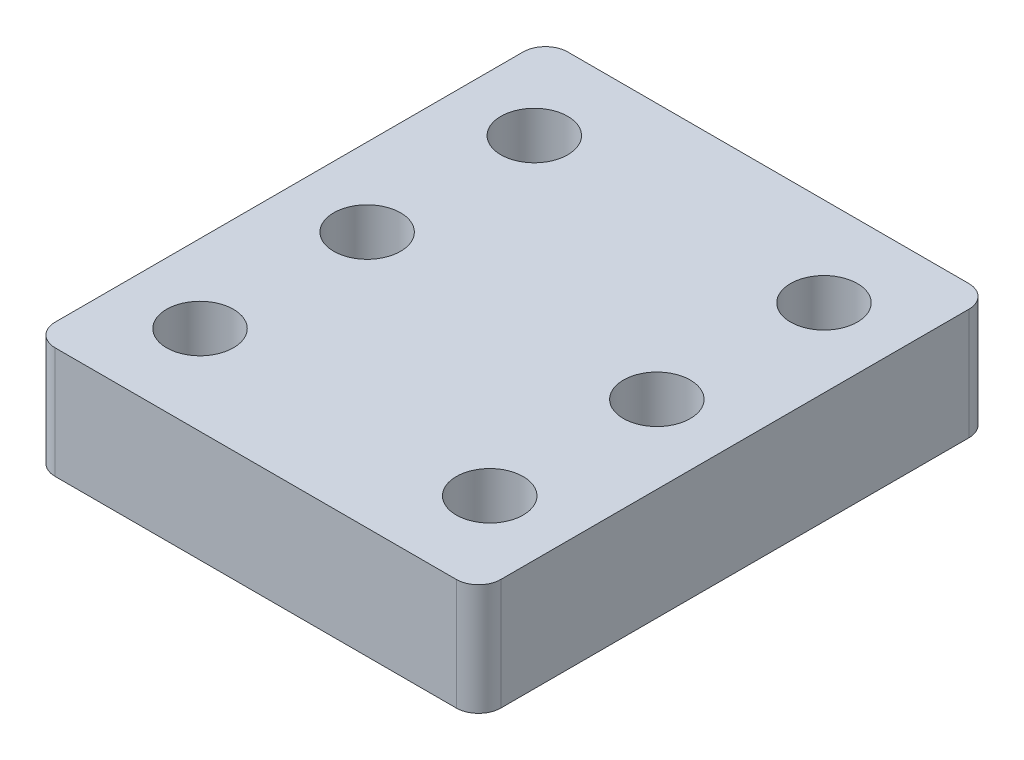
SolidWorks part; units mm, degrees
ref_plane "前视基准面" through (0, 0, 0) normal (0, 0, 1) x (1, 0, 0)
ref_plane "上视基准面" through (0, 0, 0) normal (0, 1, 0) x (1, 0, 0)
ref_plane "右视基准面" through (0, 0, 0) normal (1, 0, 0) x (0, 0, -1)
sketch "草图1" plane through (0, 0, 0) normal (0, 1, 0) x (1, 0, 0)
  line L0 (0, 0) -> (-6.5, 0) construction
  line L1 (-10, 11.5) -> (10, 11.5)
  line L2 (-10, 11.5) -> (-10, -11.5)
  line L3 (-10, -11.5) -> (10, -11.5)
  line L4 (10, 11.5) -> (10, -11.5)
  line L5 (-10, 11.5) -> (10, -11.5) construction
  line L6 (-10, -11.5) -> (10, 11.5) construction
  line L7 (-6.5, 0) -> (-6.5, -7.5) construction
  line L8 (0, 11.5) -> (0, -11.5) construction
  line L9 (6.5, 0) -> (6.5, -7.5) construction
  circle A0 centre (-6.5, 0) radius 1.5
  circle A1 centre (-6.5, -7.5) radius 1.5
  circle A2 centre (-6.5, 7.5) radius 1.5
  circle A3 centre (6.5, 7.5) radius 1.5
  circle A4 centre (6.5, -7.5) radius 1.5
  circle A5 centre (6.5, 0) radius 1.5
  point P0 (0, 0)
  dimension "D1" = 3
  dimension "D2" = 3
  dimension "D5" = 15
  dimension "D3" = 23
  dimension "D4" = 20
  dimension "D6" = 13
extrude "凸台-拉伸1" add sketch "草图1" along normal blind 5
fillet "圆角1" radius 1 4 edges at (10, 2.5, -11.5) (10, 2.5, 11.5) (-10, 2.5, 11.5) (-10, 2.5, -11.5)
